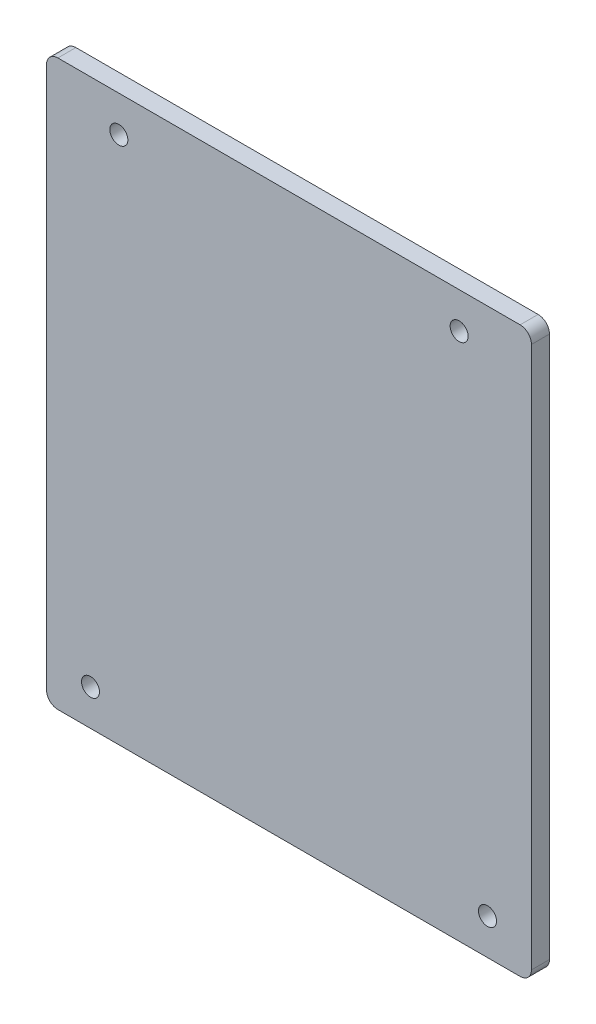
SolidWorks part; units mm, degrees
ref_plane "Front Plane" through (0, 0, 0) normal (0, 0, 1) x (1, 0, 0)
ref_plane "Top Plane" through (0, 0, 0) normal (0, 1, 0) x (1, 0, 0)
ref_plane "Right Plane" through (0, 0, 0) normal (1, 0, 0) x (0, 0, -1)
sketch "Sketch1" plane through (0, 0, 0) normal (0, 0, 1) x (1, 0, 0)
  line L0 (-42.75, -12.7) -> (42.75, -12.7) construction
  line L5 (-40.75, 0) -> (40.75, 0)
  line L6 (-42.75, -2) -> (-42.75, -97.5)
  line L7 (-40.75, -99.5) -> (40.75, -99.5)
  line L8 (42.75, -2) -> (42.75, -97.5)
  line L9 (-42.75, -86.8) -> (42.75, -86.8) construction
  arc A4 (40.75, -99.5) -> (42.75, -97.5) centre (40.75, -97.5) ccw
  arc A5 (-42.75, -97.5) -> (-40.75, -99.5) centre (-40.75, -97.5) ccw
  arc A6 (40.75, 0) -> (42.75, -2) centre (40.75, -2) cw
  arc A7 (-40.75, 0) -> (-42.75, -2) centre (-40.75, -2) ccw
  circle A8 centre (-30, -6.35) radius 1.5875
  circle A9 centre (30, -6.35) radius 1.5875
  circle A10 centre (35, -93.15) radius 1.5875
  circle A11 centre (-35, -93.15) radius 1.5875
  point P8 (-42.75, -99.5)
  point P11 (42.75, 0)
  point P14 (-42.75, 0)
  point P24 (0, 0)
  point P29 (0, 0)
  point P30 (0, 0)
  dimension "D3" = 2
  dimension "D4" = 12.7
  dimension "D5" = 3.175
  dimension "D6" = 3.175
  dimension "D12" = 3.175
  dimension "D13" = 3.175
  dimension "D14" = 70
  dimension "D1" = 85.5
  dimension "D2" = 99.5
  dimension "D7" = 6.35
  dimension "D8" = 60
  dimension "D9" = 12.75
  dimension "D10" = 12.7
  dimension "D11" = 6.35
  dimension "D15" = 7.75
extrude "Boss-Extrude1" add sketch "Sketch1" along normal blind 3.175
